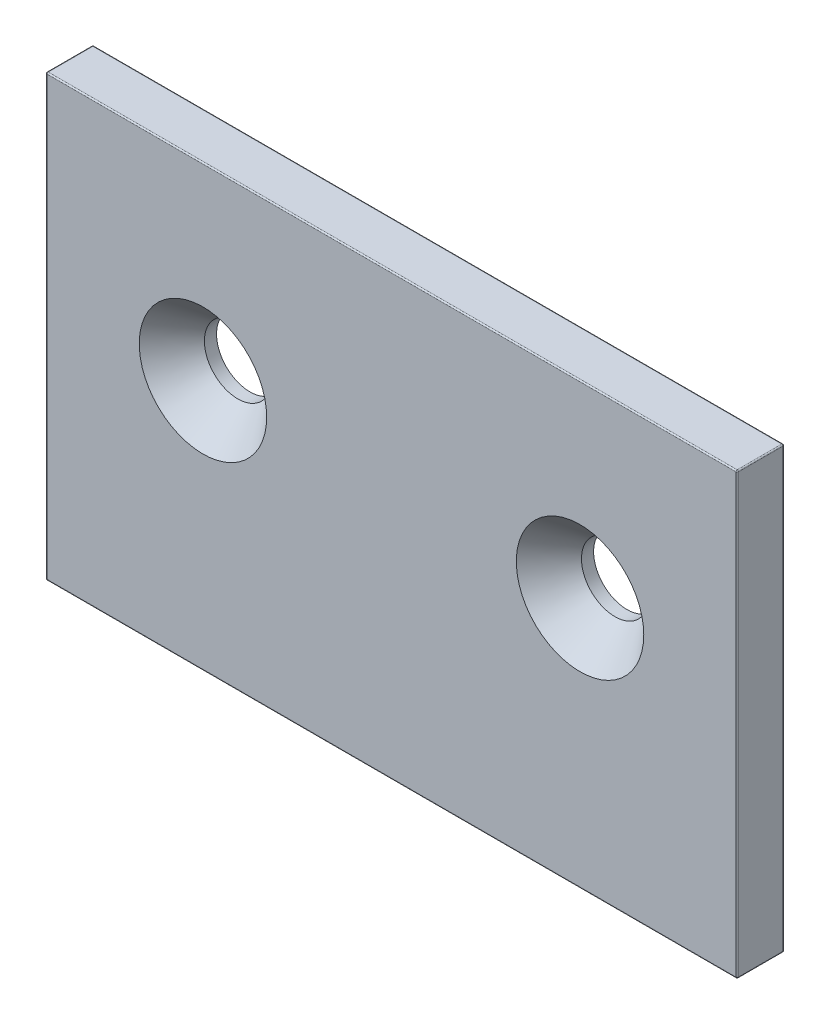
SolidWorks part; units mm, degrees
ref_plane "Front Plane" through (0, 0, 0) normal (0, 0, 1) x (1, 0, 0)
ref_plane "Top Plane" through (0, 0, 0) normal (0, 1, 0) x (1, 0, 0)
ref_plane "Right Plane" through (0, 0, 0) normal (1, 0, 0) x (0, 0, -1)
sketch "Sketch1" plane through (0, 0, 0) normal (0, 0, 1) x (1, 0, 0)
  line L1 (-34.925, 44.45) -> (34.925, 44.45)
  line L2 (-34.925, 44.45) -> (-34.925, 0)
  line L3 (-34.925, 0) -> (34.925, 0)
  line L4 (34.925, 44.45) -> (34.925, 0)
  dimension "D1" = 69.85
  dimension "D2" = 44.45
extrude "Boss-Extrude1" add sketch "Sketch1" against normal blind 4.7498
hole_wizard "CSK for 1/4 Flat Head Machine Screw1" positions "3DSketch1" profile "Sketch3" countersink size "1/4" standard "ANSI Inch" end condition through all
sketch3d "3DSketch1"
  line L0 (0, 0, 0) -> (0, 25.4, 0) construction
  line L1 (-34.925, 0, 0) -> (34.925, 0, 0) construction
  point P6 (-19.05, 25.4, 0)
  point P8 (19.05, 25.4, 0)
  dimension "D1" = 25.4
  dimension "D2" = 38.1
  dimension "D3" = 19.05
sketch "Sketch3" plane through (19.05, 25.4, 0) normal (1, 0, 0) x (0, -1, 0)
  line L0 (0, 0) -> (0, 4.7498)
  line L1 (0, 4.7498) -> (3.3782, 4.7498)
  line L2 (3.3782, 4.7498) -> (3.3782, 3.5209)
  line L3 (3.3782, 3.5209) -> (6.4389, 0)
  line L5 (6.4389, 0) -> (0, 0)
  line L6 (-3.3782, 3.5209) -> (-6.4389, 0) construction
  line L11 (0, -6.35) -> (0, 107.95) construction
  dimension "Thru Hole Dia." = 6.7564
  dimension "Thru Hole Depth" = 4.7498
  dimension "Near C'Sink Dia." = 12.8778
  dimension "Near C'Sink Angle" = 82
fillet "Fillet1" radius 0.127 12 edges at (-34.925, 22.225, -4.7498) (-34.925, 22.225, 0) (34.925, 22.225, -4.7498) (34.925, 22.225, 0) (34.925, 0, -2.3749) (0, 0, -4.7498) (-34.925, 0, -2.3749) (0, 0, 0) (-34.925, 44.45, -2.3749) (0, 44.45, -4.7498) (34.925, 44.45, -2.3749) (0, 44.45, 0)
